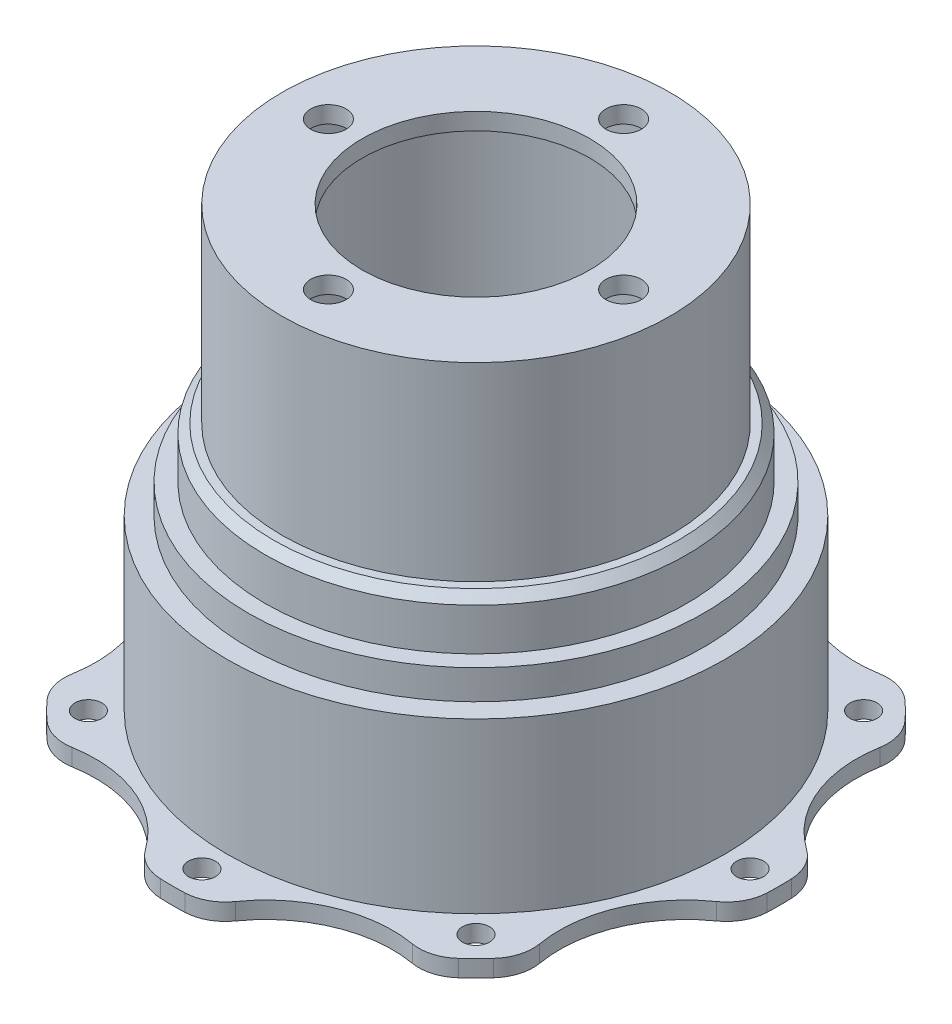
SolidWorks part; units mm, degrees
material "6060 合金"
ref_plane "前视基准面" through (0, 0, 0) normal (0, 0, 1) x (1, 0, 0)
ref_plane "上视基准面" through (0, 0, 0) normal (0, 1, 0) x (1, 0, 0)
ref_plane "右视基准面" through (0, 0, 0) normal (1, 0, 0) x (0, 0, -1)
sketch "草图1" plane through (0, 0, 0) normal (0, 1, 0) x (1, 0, 0)
  circle A0 centre (0, 0) radius 13.5
  circle A1 centre (0, 0) radius 17.5 construction
  circle A2 centre (0, 0) radius 21.5 construction
  circle A3 centre (0, 0) radius 23
  dimension "D1" = 27
  dimension "D2" = 35
  dimension "D3" = 43
  dimension "D4" = 46
extrude "凸台-拉伸1" add sketch "草图1" along normal blind 2
sketch "草图2" plane through (0, 2, 0) normal (0, 1, 0) x (1, 0, 0)
  line L0 (0, 17.5) -> (0, 0) construction
  circle A0 centre (0, 17.5) radius 2.1
  dimension "D1" = 4.2
  dimension "D2" = 17.5
extrude "切除-拉伸1" cut sketch "草图2" against normal blind 3
pattern_circular "阵列(圆周)1" count 4 over 360 about axis through (0, 0, 0) along (0, 1, 0) of "切除-拉伸1"
sketch "草图3" plane through (0, 0, 0) normal (0, -1, 0) x (1, 0, 0)
  circle A0 centre (0, 0) radius 21.25
  circle A1 centre (0, 0) radius 23
  circle A2 centre (0, 0) radius 23 construction
  dimension "D1" = 42.5
extrude "凸台-拉伸2" add sketch "草图3" along normal blind 32
sketch "草图4" plane through (0, -32, 0) normal (0, -1, 0) x (1, 0, 0)
  circle A0 centre (0, 0) radius 21.5
  circle A1 centre (0, 0) radius 29.5
  dimension "D1" = 43
  dimension "D2" = 59
extrude "凸台-拉伸3" add sketch "草图4" against normal blind 2
sketch "草图5" plane through (0, -32, 0) normal (0, -1, 0) x (1, 0, 0)
  circle A0 centre (0, 0) radius 27.5
  circle A1 centre (0, 0) radius 29.5
  dimension "D1" = 55
  dimension "D2" = 59
extrude "凸台-拉伸4" add sketch "草图5" along normal blind 20
sketch "草图6" plane through (0, -52, 0) normal (0, -1, 0) x (1, 0, 0)
  circle A0 centre (0, 0) radius 29
  circle A1 centre (0, 0) radius 36
  circle A2 centre (0, 32.5) radius 3.25 construction
  dimension "D1" = 6.5
  dimension "D2" = 72
  dimension "D3" = 58
  dimension "D4" = 32.5
extrude "凸台-拉伸5" add sketch "草图6" against normal blind 2
sketch "草图7" plane through (0, -50, 0) normal (0, 1, 0) x (1, 0, 0)
  line L0 (0, 32.5) -> (0, 0) construction
  circle A0 centre (0, 32.5) radius 1.6
  dimension "D1" = 3.2
  dimension "D2" = 32.5
extrude "切除-拉伸2" cut sketch "草图7" against normal blind 3
pattern_circular "阵列(圆周)2" count 8 over 360 about axis through (0, 0, 0) along (0, 1, 0) of "切除-拉伸2"
sketch "草图8" plane through (0, -30, 0) normal (0, 1, 0) x (1, 0, 0)
  circle A0 centre (0, 0) radius 25
  circle A1 centre (0, 0) radius 23 construction
  circle A2 centre (0, 0) radius 23
  dimension "D1" = 50
extrude "凸台-拉伸6" add sketch "草图8" along normal blind 9.5
sketch "草图9" plane through (0, -30, 0) normal (0, 1, 0) x (1, 0, 0)
  circle A0 centre (0, 0) radius 25
  circle A1 centre (0, 0) radius 27
  dimension "D1" = 54
extrude "凸台-拉伸7" add sketch "草图9" along normal blind 3.5
chamfer "倒角1" distance 1 angle 45 1 edges at (0, -20.5, 25)
sketch "草图12" plane through (0, -50, 0) normal (0, 1, 0) x (1, 0, 0)
  line L0 (0, 0) -> (17.6034, 42.4985) construction
  line L1 (0, 0) -> (0, 8.0469) construction
  line L2 (11.8632, 28.6403) -> (2.6933, 32.4386) construction
  circle A0 centre (17.6034, 42.4985) radius 15
  dimension "D2" = 31
  dimension "D3" = 30
  dimension "D4" = 46
  dimension "D1" = 22.5
extrude "切除-拉伸4" cut sketch "草图12" against normal blind 10
fillet "圆角2" radius 5 2 edges at (22.3078, -51, -28.2553) (4.2055, -51, -35.7535)
pattern_circular "阵列(圆周)4" count 8 over 360 about axis through (0, 0, 0) along (0, 1, 0) of "圆角2", "切除-拉伸4"
